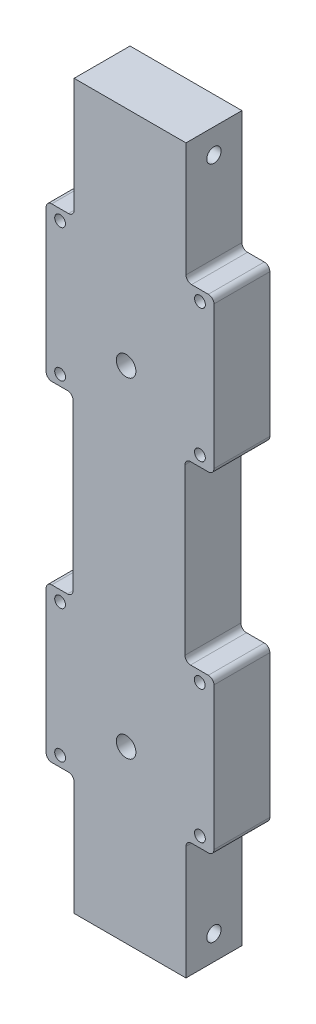
SolidWorks part; units mm, degrees
material "6063-T6"
ref_plane "Front Plane" through (0, 0, 0) normal (1, 0, 0) x (0, 1, 0)
ref_plane "Top Plane" through (0, 0, 0) normal (0, 0, 1) x (0, 1, 0)
ref_plane "Right Plane" through (0, 0, 0) normal (0, 1, 0) x (-1, 0, 0)
sketch "Sketch1" plane through (0, 0, 0) normal (0, 0, 1) x (0, 1, 0)
  line L1 (-34.925, -38.1) -> (34.925, -38.1)
  line L2 (-34.925, -38.1) -> (-34.925, 38.1)
  line L3 (-34.925, 38.1) -> (34.925, 38.1)
  line L4 (34.925, -38.1) -> (34.925, 38.1)
  line L5 (-34.925, -38.1) -> (34.925, 38.1) construction
  line L6 (-34.925, 38.1) -> (34.925, -38.1) construction
  circle A0 centre (-11.811, 1.778) radius 4.445
  point P0 (0, 0)
  dimension "D3" = 8.89
  dimension "D1" = 76.2
  dimension "D2" = 69.85
  dimension "D4" = 46.736
  dimension "D5" = 36.322
extrude "Boss-Extrude1" add sketch "Sketch1" along normal blind 25.4
sketch "Sketch2" plane through (0, 0, 0) normal (0, 0, -1) x (1, 0, 0)
  line L0 (-38.1, -34.925) -> (-38.1, 34.925) construction
  line L1 (-25.4, 27.686) -> (25.4, 27.686)
  line L2 (-25.4, 27.686) -> (-25.4, -22.225)
  line L3 (-25.4, -22.225) -> (25.4, -22.225)
  line L4 (25.4, 27.686) -> (25.4, -22.225)
  line L6 (38.1, 34.925) -> (38.1, -34.925) construction
  line L7 (38.1, -34.925) -> (-38.1, -34.925) construction
  line L8 (-1.778, 16.256) -> (-1.778, 7.366) construction
  line L9 (-6.223, 11.811) -> (2.667, 11.811) construction
  circle A0 centre (-1.778, 11.811) radius 4.445 construction
  point P17 (-1.778, 11.811)
  dimension "D1" = 12.7
  dimension "D3" = 12.7
  dimension "D4" = 12.7
  dimension "D2" = 15.875
extrude "Cut-Extrude1" cut sketch "Sketch2" against normal blind 15.875
sketch "Sketch4" plane through (0, 34.925, 0) normal (0, 1, 0) x (-1, 0, 0)
  line L0 (-38.1, 25.4) -> (38.1, 25.4) construction
  line L1 (-24.9341, 25.4) -> (25.8659, 25.4)
  line L2 (-24.9341, 25.4) -> (-24.9341, 0)
  line L3 (-24.9341, 0) -> (25.8659, 0)
  line L4 (25.8659, 25.4) -> (25.8659, 0)
  line L5 (-38.1, 0) -> (38.1, 0) construction
  line L6 (0.4659, 25.4) -> (0.4659, 0) construction
  dimension "D1" = 50.8
extrude "Boss-Extrude2" add sketch "Sketch4" along normal blind 79.9846
sketch "Sketch7" plane through (0, 114.9096, 0) normal (0, 1, 0) x (-1, 0, 0)
  line L0 (25.8659, 0) -> (38.1, 0) construction
  line L1 (-38.1, 25.4) -> (38.1, 25.4)
  line L2 (-38.1, 25.4) -> (-38.1, 0)
  line L3 (-38.1, 0) -> (38.1, 0)
  line L4 (38.1, 25.4) -> (38.1, 0)
extrude "Boss-Extrude5" add sketch "Sketch7" along normal blind 69.85
sketch "Sketch10" plane through (0, 0, 25.4) normal (0, 0, 1) x (1, 0, 0)
  line L0 (-38.1, 184.7596) -> (38.1, 184.7596) construction
  line L1 (-38.1, 184.7596) -> (-38.1, 114.9096) construction
  circle A0 centre (-1.778, 138.0236) radius 4.445
  dimension "D3" = 8.89
  dimension "D1" = 46.736
  dimension "D2" = 36.322
extrude "Cut-Extrude3" cut sketch "Sketch10" against normal through all
sketch "Sketch11" plane through (0, 0, 0) normal (0, 0, -1) x (1, 0, 0)
  line L1 (-25.4, -122.1486) -> (25.4, -122.1486)
  line L2 (-25.4, -122.1486) -> (-25.4, -172.0596)
  line L3 (-25.4, -172.0596) -> (25.4, -172.0596)
  line L4 (25.4, -122.1486) -> (25.4, -172.0596)
  line L6 (38.1, -184.7596) -> (38.1, -114.9096) construction
  line L8 (-38.1, -184.7596) -> (-38.1, -114.9096) construction
  line L9 (38.1, -184.7596) -> (-38.1, -184.7596) construction
  line L10 (2.667, -138.0236) -> (-6.223, -138.0236) construction
  line L11 (-1.778, -133.5786) -> (-1.778, -142.4686) construction
  circle A0 centre (-1.778, -138.0236) radius 4.445 construction
  point P17 (-1.778, -138.0236)
  dimension "D1" = 12.7
  dimension "D3" = 12.7
  dimension "D4" = 12.7
  dimension "D2" = 15.875
extrude "Cut-Extrude4" cut sketch "Sketch11" against normal blind 15.875
sketch "Sketch12" plane through (0, 184.7596, 0) normal (0, 1, 0) x (-1, 0, 0)
  line L0 (38.1, 25.4) -> (-38.1, 25.4) construction
  line L1 (-25.4, 25.4) -> (25.4, 25.4)
  line L2 (-25.4, 25.4) -> (-25.4, 0)
  line L3 (-25.4, 0) -> (25.4, 0)
  line L4 (25.4, 25.4) -> (25.4, 0)
  line L5 (-38.1, 0) -> (38.1, 0) construction
  dimension "D1" = 25.4
  dimension "D2" = 50.8
extrude "Boss-Extrude7" add sketch "Sketch12" along normal blind 54.4576
sketch "Sketch13" plane through (0, -34.925, 0) normal (0, -1, 0) x (1, 0, 0)
  line L0 (-38.1, 25.4) -> (38.1, 25.4) construction
  line L1 (-25.4, 25.4) -> (25.4, 25.4)
  line L2 (-25.4, 25.4) -> (-25.4, 0)
  line L3 (-25.4, 0) -> (25.4, 0)
  line L4 (25.4, 25.4) -> (25.4, 0)
  line L5 (-38.1, 0) -> (38.1, 0) construction
  dimension "D1" = 25.4
  dimension "D2" = 50.8
extrude "Boss-Extrude8" add sketch "Sketch13" along normal blind 54.2798
hole_wizard "#10 (0.1935) Diameter Hole2" positions "Sketch14" profile "Sketch16" hole size "#10" standard "ANSI Inch"
sketch "Sketch14" plane through (0, 0, 25.4) normal (0, 0, 1) x (1, 0, 0)
  line L0 (24.9341, 114.9096) -> (38.1, 114.9096) construction
  line L1 (-38.1, 184.7596) -> (-38.1, 114.9096) construction
  point P0 (31.75, 119.6721)
  point P2 (31.75, 179.9971)
  point P4 (-31.75, 179.9971)
  point P6 (-31.75, 119.6721)
  dimension "D1" = 60.325
  dimension "D2" = 63.5
  dimension "D3" = 4.7625
  dimension "D4" = 6.35
sketch "Sketch16" plane through (31.75, 119.6721, 25.4) normal (1, 0, 0) x (0, -1, 0)
  line L0 (0, 0) -> (0, 13.4146)
  line L1 (0, 13.4146) -> (2.4574, 11.938)
  line L2 (2.4574, 11.938) -> (2.4574, 0)
  line L5 (2.4574, 0) -> (0, 0)
  line L10 (0, 13.4146) -> (-2.4575, 11.938) construction
  line L11 (0, -6.35) -> (0, 107.95) construction
  dimension "Hole Dia." = 4.9149
  dimension "Hole Depth" = 11.938
  dimension "Drill Angle" = 118
sketch "Sketch18" plane through (25.4, 0, 0) normal (1, 0, 0) x (0, 1, 0)
  line L0 (184.7596, 12.7) -> (239.2172, 12.7) construction
  line L1 (184.7596, 25.4) -> (184.7596, 0) construction
  line L2 (239.2172, 25.4) -> (239.2172, 0) construction
  circle A0 centre (228.1047, 12.7) radius 3.2639
  dimension "D1" = 6.5278
  dimension "D2" = 11.1125
extrude "Cut-Extrude5" cut sketch "Sketch18" against normal blind 12.7
sketch "Sketch19" plane through (-25.4, 0, 0) normal (-1, 0, 0) x (0, -1, 0)
  line L0 (-239.2172, 12.7) -> (-184.7596, 12.7) construction
  line L1 (-239.2172, 0) -> (-239.2172, 25.4) construction
  line L2 (-184.7596, 0) -> (-184.7596, 25.4) construction
  circle A0 centre (-228.1047, 12.7) radius 3.2639
  dimension "D2" = 6.5278
  dimension "D1" = 11.1125
extrude "Cut-Extrude6" cut sketch "Sketch19" against normal blind 12.7
sketch "Sketch20" plane through (-25.4, 0, 0) normal (-1, 0, 0) x (0, -1, 0)
  line L0 (34.925, 12.7) -> (89.2048, 12.7) construction
  line L1 (34.925, 25.4) -> (34.925, 0) construction
  line L2 (89.2048, 25.4) -> (89.2048, 0) construction
  circle A0 centre (78.0923, 12.7) radius 3.2639
  dimension "D2" = 6.5278
  dimension "D1" = 11.1125
extrude "Cut-Extrude7" cut sketch "Sketch20" against normal blind 12.7
sketch "Sketch21" plane through (25.4, 0, 0) normal (1, 0, 0) x (0, 1, 0)
  line L0 (-89.2048, 12.7) -> (-34.925, 12.7) construction
  line L1 (-89.2048, 0) -> (-89.2048, 25.4) construction
  line L2 (-34.925, 25.4) -> (-34.925, 0) construction
  circle A0 centre (-78.0923, 12.7) radius 3.2639
  dimension "D1" = 6.5278
  dimension "D2" = 11.1125
extrude "Cut-Extrude8" cut sketch "Sketch21" against normal blind 12.7
hole_wizard "#10 (0.1935) Diameter Hole3" positions "Sketch22" profile "Sketch23" hole size "#10" standard "ANSI Inch"
sketch "Sketch22" plane through (0, 0, 25.4) normal (0, 0, 1) x (1, 0, 0)
  line L0 (-38.1, -34.925) -> (-25.4, -34.925) construction
  line L1 (38.1, -34.925) -> (38.1, 34.925) construction
  point P0 (31.75, -30.1625)
  point P2 (31.6635, 30.1625)
  point P4 (-31.75, 30.1625)
  point P6 (-31.75, -30.1625)
  point P14 (0, 0)
  point P15 (0, 0)
  point P16 (0, 0)
  dimension "D1" = 60.325
  dimension "D2" = 63.5
  dimension "D3" = 4.7625
  dimension "D4" = 6.35
sketch "Sketch23" plane through (31.75, -30.1625, 25.4) normal (1, 0, 0) x (0, -1, 0)
  line L0 (0, 0) -> (0, 13.4146)
  line L1 (0, 13.4146) -> (2.4574, 11.938)
  line L2 (2.4574, 11.938) -> (2.4574, 0)
  line L5 (2.4574, 0) -> (0, 0)
  line L10 (0, 13.4146) -> (-2.4574, 11.938) construction
  line L11 (0, -6.35) -> (0, 107.95) construction
  dimension "Hole Dia." = 4.9149
  dimension "Hole Depth" = 11.938
  dimension "Drill Angle" = 118
fillet "Fillet1" radius 2.54 16 edges at (25.4, -34.925, 12.7) (38.1, -34.925, 12.7) (-38.1, -34.925, 12.7) (-25.4, -34.925, 12.7) (-38.1, 34.925, 12.7) (-25.8659, 34.925, 12.7) (-25.8659, 114.9096, 12.7) (-38.1, 114.9096, 12.7) (-38.1, 184.7596, 12.7) (-25.4, 184.7596, 12.7) (25.4, 184.7596, 12.7) (38.1, 184.7596, 12.7) (38.1, 114.9096, 12.7) (24.9341, 114.9096, 12.7) (38.1, 34.925, 12.7) (24.9341, 34.925, 12.7)
fillet "Fillet2" radius 2.54 8 edges at (25.4, -2.7305, 15.875) (0, 22.225, 15.875) (-25.4, -2.7305, 15.875) (0, -27.686, 15.875) (0, 122.1486, 15.875) (-25.4, 147.1041, 15.875) (0, 172.0596, 15.875) (25.4, 147.1041, 15.875)
equation "\"D1@Sketch1\"=\"width_1\""
equation "\"width_1\"= 3"
equation "\"shaft_d1\"= 1.84"
equation "\"shaft_d2\"= 1.43"
equation "\"height\"= 1"
equation "\"bearing_len\"= 1.250"
equation "\"width_2\"= 2.75"
equation "\"screw_dist_1\"=2.5"
equation "\"screw_dist_2\"=2.375"
equation "\"shaft_hole\"= .35"
equation "\"D2@Sketch1\"=\"width_2\""
equation "\"D3@Sketch1\"=\"shaft_hole\""
equation "\"D4@Sketch1\"=\"shaft_d1\""
equation "\"D5@Sketch1\"=\"shaft_d2\""
equation "\"D1@Boss-Extrude1\"=\"height\""
equation "\"D1@Sketch2\"=.5"
equation "\"D1@Cut-Extrude1\"=\"bearing_len\"*.5"
equation "\"D2@Sketch2\"=1.250/2"
equation "\"hole_dist\"= 150mm - ( \"shaft_d1\" * 2 )"
equation "\"D1@Boss-Extrude2\"=3.149"
equation "\"D1@Boss-Extrude5\"=\"width_2\""
equation "\"D1@Sketch10\"=\"shaft_d1\""
equation "\"D2@Sketch10\"=\"shaft_d2\""
equation "\"D3@Sketch10\"=\"shaft_hole\""
equation "\"D2@Sketch11\"=1.250/2"
equation "\"D1@Cut-Extrude4\"=\"bearing_len\"/2"
equation "\"D1@Sketch14\"=\"screw_dist_2\""
equation "\"D2@Sketch14\"=\"screw_dist_1\""
equation "\"D3@Sketch14\"=(\"width_2\"-\"screw_dist_2\")/2"
equation "\"D4@Sketch14\"=(\"width_1\"-\"screw_dist_1\")/2"
equation "\"bracket_hole\"= .257"
equation "\"bracket_dist\"= .875 * .5"
equation "\"D1@Sketch18\"=\"bracket_hole\""
equation "\"D2@Sketch18\"=\"bracket_dist\""
equation "\"D1@Sketch19\"=\"bracket_dist\""
equation "\"D2@Sketch19\"=\"bracket_hole\""
equation "\"D1@Sketch20\"=\"bracket_dist\""
equation "\"D2@Sketch20\"=\"bracket_hole\""
equation "\"D1@Sketch21\"=\"bracket_hole\""
equation "\"D2@Sketch21\"=\"bracket_dist\""
equation "\"D1@Sketch22\"=\"screw_dist_2\""
equation "\"D2@Sketch22\"=\"screw_dist_1\""
equation "\"D3@Sketch22\"=(\"width_2\"-\"screw_dist_2\")/2"
equation "\"D4@Sketch22\"=(\"width_1\"-\"screw_dist_1\")/2"
